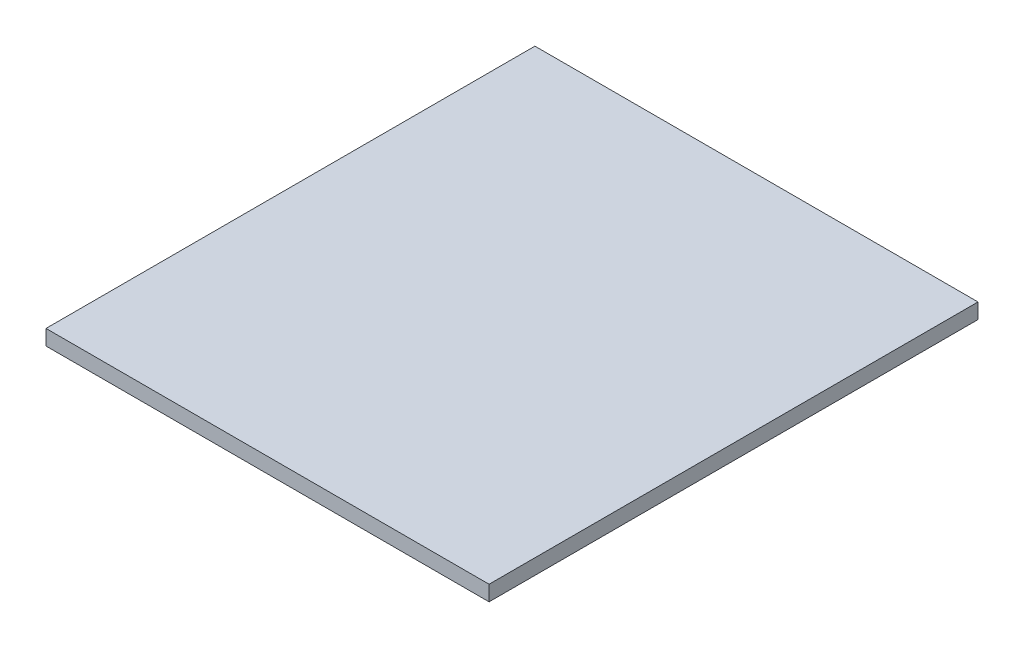
SolidWorks part; units mm, degrees
ref_plane "Спереди" through (0, 0, 0) normal (0, 0, 1) x (1, 0, 0)
ref_plane "Сверху" through (0, 0, 0) normal (0, 1, 0) x (1, 0, 0)
ref_plane "Справа" through (0, 0, 0) normal (1, 0, 0) x (0, 0, -1)
sketch "Эскиз1" plane through (0, 0, 0) normal (0, 1, 0) x (1, 0, 0)
  line L1 (0, 0) -> (290, 0)
  line L2 (0, 0) -> (0, 320)
  line L3 (0, 320) -> (290, 320)
  line L4 (290, 0) -> (290, 320)
  dimension "D1" = 290
  dimension "D2" = 320
extrude "Нижняя панель стола" add sketch "Эскиз1" along normal blind 10
